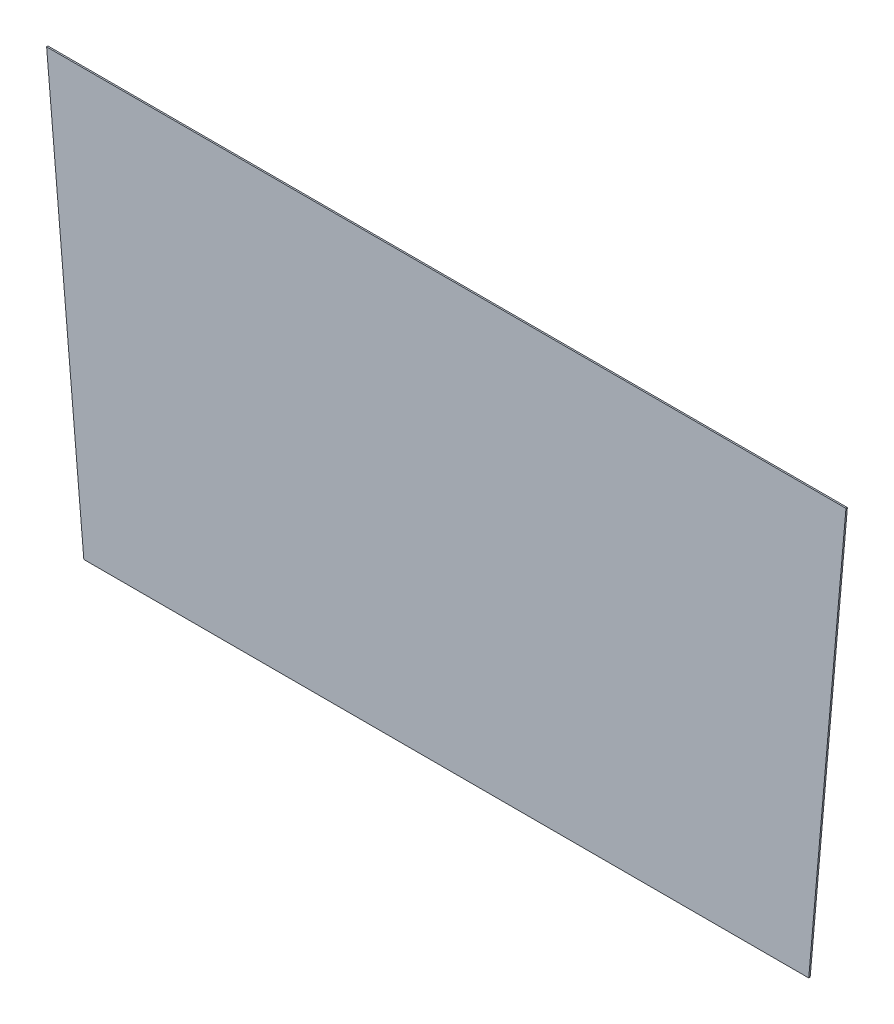
SolidWorks part; units mm, degrees
ref_plane "Front Plane" through (0, 0, 0) normal (0, 0, 1) x (1, 0, 0)
ref_plane "Top Plane" through (0, 0, 0) normal (0, 1, 0) x (1, 0, 0)
ref_plane "Right Plane" through (0, 0, 0) normal (1, 0, 0) x (0, 0, -1)
sketch "Sketch1" plane through (4.4989, 0, 0) normal (0, 0, 1) x (1, 0, 0)
  line L0 (-456.8259, 197.5314) -> (385.6143, 197.5314)
  line L1 (385.6143, 197.5314) -> (346.3942, -250.7562)
  line L2 (346.3942, -250.7562) -> (-417.6058, -250.7562)
  line L3 (-417.6058, -250.7562) -> (-456.8259, 197.5314)
  dimension "D1" = 764
  dimension "D2" = 95
  dimension "D3" = 95
  dimension "D4" = 450
extrude "Boss-Extrude1" add sketch "Sketch1" along normal blind 1.5
